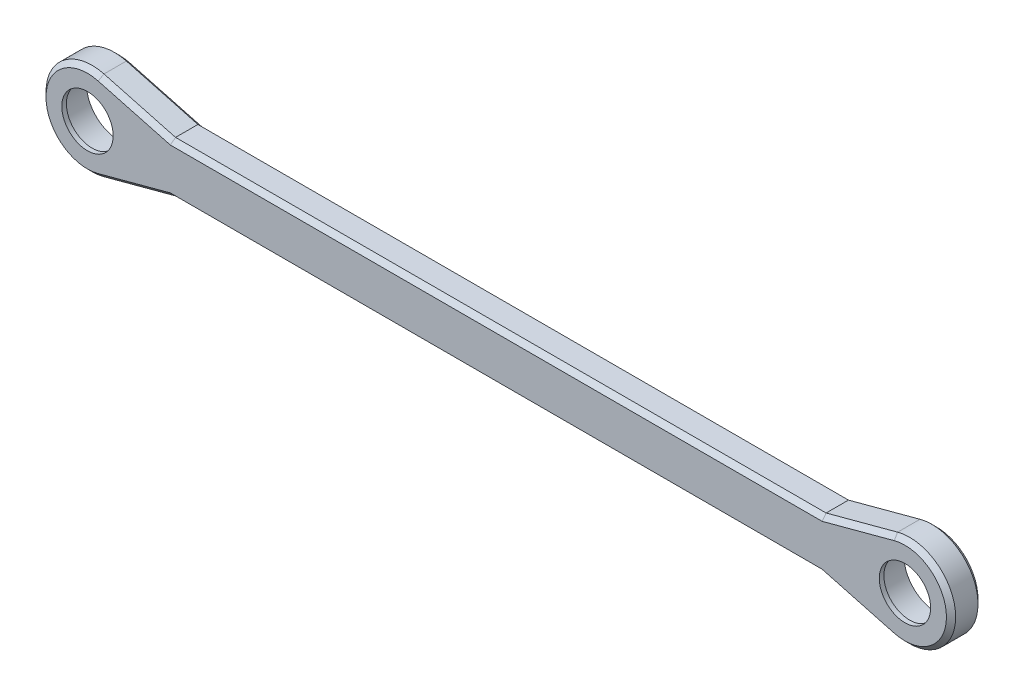
SolidWorks part; units mm, degrees
ref_plane "前视基准面" through (0, 0, 0) normal (0, 0, 1) x (1, 0, 0)
ref_plane "上视基准面" through (0, 0, 0) normal (0, 1, 0) x (1, 0, 0)
ref_plane "右视基准面" through (0, 0, 0) normal (1, 0, 0) x (0, 0, -1)
other "Configuration Table"
sketch "草图1" plane through (0, 0, 0) normal (0, 0, 1) x (1, 0, 0)
  line L0 (0, 0) -> (177.4, 0) construction
  line L1 (8.3516, 5.5) -> (169.0484, 5.5)
  line L2 (8.3516, -5.5) -> (169.0484, -5.5)
  line L3 (2.5882, 9.6593) -> (18.1108, 5.5)
  line L4 (2.5882, -9.6593) -> (18.1108, -5.5)
  line L5 (174.8118, -9.6593) -> (159.2892, -5.5)
  line L6 (174.8118, 9.6593) -> (159.2892, 5.5)
  circle A0 centre (0, 0) radius 10
  circle A1 centre (0, 0) radius 7.075
  circle A2 centre (177.4, 0) radius 7.075
  circle A3 centre (177.4, 0) radius 10
  dimension "D1" = 20
  dimension "D2" = 14.15
  dimension "D4" = 14.15
  dimension "D5" = 20
  dimension "D3" = 177.4
  dimension "D6" = 5.5
  dimension "D7" = 5.5
  dimension "D8" = 15
  dimension "D9" = 15
  dimension "D10" = 15
  dimension "D11" = 15
extrude "凸台-拉伸1" add sketch "草图1" along normal blind 6.85
sketch "草图2" plane through (0, 0, 6.85) normal (0, 0, 1) x (1, 0, 0)
  circle A0 centre (0, 0) radius 5.575
  circle A1 centre (0, 0) radius 7.075 construction
  circle A2 centre (0, 0) radius 7.075
  circle A3 centre (177.4, 0) radius 7.075 construction
  circle A4 centre (177.4, 0) radius 7.075
  circle A5 centre (177.4, 0) radius 5.575
  dimension "D1" = 1.5
  dimension "D2" = 1.5
extrude "凸台-拉伸2" add sketch "草图2" against normal blind 1
chamfer "倒角1" distance 1 angle 45 16 edges at (167.0505, -7.5796, 0) (167.0505, -7.5796, 6.85) (167.0505, 7.5796, 0) (167.0505, 7.5796, 6.85) (187.4, 0, 0) (187.4, 0, 6.85) (88.7, 5.5, 0) (88.7, 5.5, 6.85) (10.3495, 7.5796, 0) (10.3495, 7.5796, 6.85) (-10, 0, 0) (-10, 0, 6.85) (88.7, -5.5, 0) (88.7, -5.5, 6.85) (10.3495, -7.5796, 0) (10.3495, -7.5796, 6.85)
